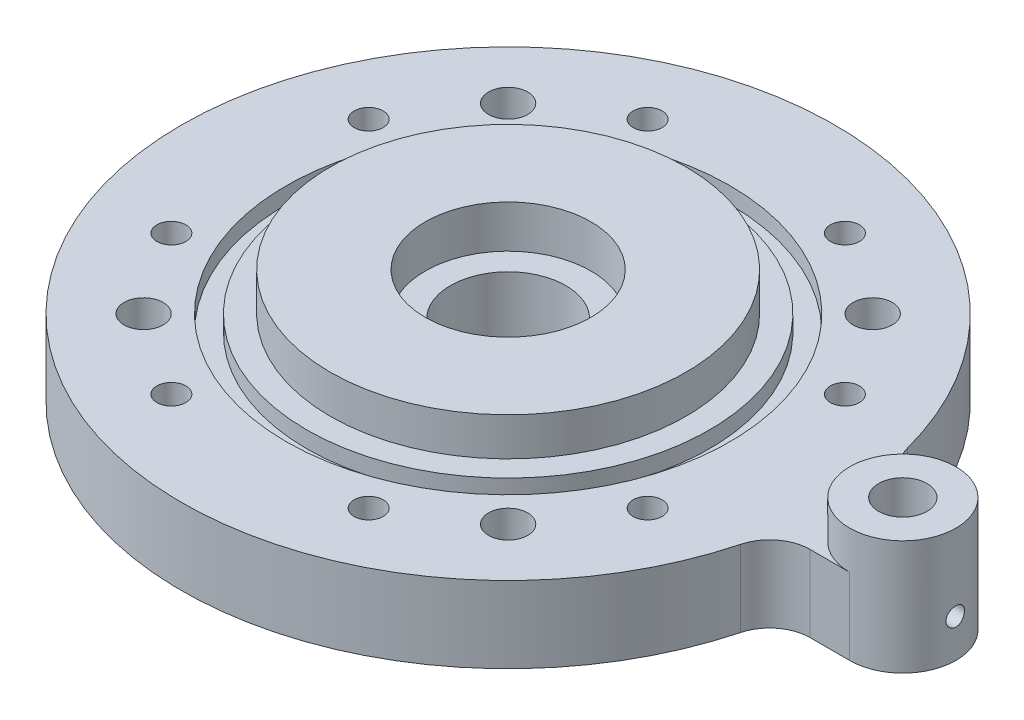
SolidWorks part; units mm, degrees
material "1060 Alloy"
ref_plane "Front" through (0, 0, 0) normal (0, 0, 1) x (1, 0, 0)
ref_plane "Top" through (0, 0, 0) normal (0, 1, 0) x (1, 0, 0)
ref_plane "Right" through (0, 0, 0) normal (1, 0, 0) x (0, 0, -1)
sketch "Sketch1" plane through (0, 0, 0) normal (0, 1, 0) x (1, 0, 0)
  line L0 (58.8962, 0) -> (68.0634, 0) construction
  line L1 (61.2588, 9.1672) -> (68.0634, 9.1672)
  line L2 (61.2588, -9.1672) -> (68.0634, -9.1672)
  line L3 (58.8962, 0) -> (77.2306, 0) construction
  line L4 (58.8962, 0) -> (56.3562, 0) construction
  arc A0 (54.4905, 14.3809) -> (54.4905, -14.3809) centre (0, 0) ccw
  circle A1 centre (0, 0) radius 56.3562 construction
  arc A2 (68.0634, -9.1672) -> (68.0634, 9.1672) centre (68.0634, 0) ccw
  arc A3 (54.4905, 14.3809) -> (61.2588, 9.1672) centre (61.2588, 16.1672) ccw
  arc A4 (61.2588, -9.1672) -> (54.4905, -14.3809) centre (61.2588, -16.1672) ccw
  point P5 (34.5422, 0)
  point P10 (55.6057, 9.1672)
  dimension "D1" = 112.7125
  dimension "D4" = 7
  dimension "D2" = 18.3344
  dimension "D3" = 18.3344
  dimension "D5" = 2.54
extrude "base" add sketch "Sketch1" along normal blind 13.175
sketch "Sketch2" plane through (0, 13.175, 0) normal (0, 1, 0) x (1, 0, 0)
  line L0 (68.0634, 9.1672) -> (68.0634, -9.1672) construction
  circle A0 centre (0, 0) radius 30.6705
  arc A1 (68.0634, -9.1672) -> (68.0634, 9.1672) centre (68.0634, 0) ccw construction
  circle A2 centre (68.0634, 0) radius 9.1672
  circle A3 centre (68.0634, 0) radius 4.1672
  dimension "D1" = 61.341
  dimension "D2" = 8.3344
sketch "Sketch3" plane through (0, 0, 0) normal (0, -1, 0) x (1, 0, 0)
  line L0 (0, 0) -> (77.2306, 0) construction
  line L1 (0, 0) -> (39.8499, -39.8499) construction
  circle A0 centre (0, 0) radius 44.45 construction
  circle A1 centre (-31.4309, -31.4309) radius 3.3734
  circle A2 centre (-31.4309, 31.4309) radius 3.3734
  circle A3 centre (31.4309, 31.4309) radius 3.3734
  circle A4 centre (31.4309, -31.4309) radius 3.3734
  arc A5 (68.0634, -9.1672) -> (68.0634, 9.1672) centre (68.0634, 0) ccw construction
  arc A6 (54.4905, 14.3809) -> (54.4905, -14.3809) centre (0, 0) ccw construction
  point P14 (0, 0)
  dimension "D1" = 88.9
  dimension "D2" = 6.7469
  dimension "D4" = 45
  dimension "D3" = 4
extrude "square bolt holes" cut sketch "Sketch3" against normal through all
sketch "Sketch4" plane through (0, 13.175, 0) normal (0, 1, 0) x (1, 0, 0)
  line L0 (0, 0) -> (0, 44.45) construction
  line L1 (0, 44.45) -> (0, 0) construction
  line L2 (0, 0) -> (17.0103, 41.0664) construction
  circle A0 centre (0, 0) radius 44.45 construction
  circle A1 centre (17.0103, 41.0664) radius 2.5
  dimension "D1" = 88.9
  dimension "D3" = 5
  dimension "D2" = 22.5
extrude "housing bolts" cut sketch "Sketch4" against normal blind 44.33
pattern_circular "CirPattern1" count 8 over 360 about axis through (0, 0, 0) along (0, 1, 0) of "housing bolts"
extrude "impeller cavity riser" add sketch "Sketch2" along normal blind 6.59
sketch "Sketch5" plane through (0, 19.765, 0) normal (0, 1, 0) x (1, 0, 0)
  circle A0 centre (0, 0) radius 14.2875
  dimension "D1" = 28.575
extrude "seal bore" cut sketch "Sketch5" against normal blind 7.35
sketch "Sketch6" plane through (0, 12.415, 0) normal (0, 1, 0) x (1, 0, 0)
  circle A0 centre (0, 0) radius 9.9375
  dimension "D1" = 19.875
extrude "bore" cut sketch "Sketch6" against normal blind 39.3
sketch "pressure tap plane alignment" plane through (0, 0, 0) normal (0, -1, 0) x (1, 0, 0)
  line L1 (0, 0) -> (56.3562, 0) construction
  line L2 (56.3562, 0) -> (56.3562, 56.3563) construction
  line L3 (56.3562, 56.3563) -> (0, 56.3562) construction
  circle A0 centre (0, 0) radius 56.3562 construction
  circle A1 centre (0, 0) radius 56.3562 construction
ref_plane "pressure tap plane" through (56.3562, 0, 0) normal (1, 0, 0) x (0, 0, -1)
sketch "Sketch9" plane through (56.3562, 0, 0) normal (1, 0, 0) x (0, 0, -1)
  line L0 (0, 0) -> (0, 13.175) construction
  line L1 (56.3562, 13.175) -> (-56.3563, 13.175) construction
  circle A0 centre (0, 6.5875) radius 1.5875
  dimension "D1" = 3.175
extrude "pressure tap" cut sketch "Sketch9" against normal blind 56.3562 and the other way through all
sketch "Sketch10" plane through (0, 13.175, 0) normal (0, 1, 0) x (1, 0, 0)
  circle A0 centre (68.0634, 0) radius 1.5875
  dimension "D1" = 3.175
extrude "pressure tap vertical hole" cut sketch "Sketch10" against normal blind 8.175
sketch "Sketch12" plane through (0, 13.175, 0) normal (0, 1, 0) x (1, 0, 0)
  circle A0 centre (0, 0) radius 34.7218
  circle A1 centre (0, 0) radius 38.2524
  dimension "D1" = 76.5048
  dimension "D2" = 69.4436
extrude "Cut-Extrude1" cut sketch "Sketch12" against normal blind 2.8245
equation "\"de\" = 0.43in\t\t\t'entrance eye diameter"
equation "\"d2\" = 2.1in \t\t\t'outer diameter of the impeller"
equation "\"d_exit\" = 0.18in \t\t'throat aka d1"
equation "\"theta\" = 12\t\t\t'angle of blades from inner to outer "
equation "\"impeller upper clearance\"= .5mm"
equation "\"impeller horizontal clearance\"= (\"d2\"*1.15 - \"d2\")/2 \t\t'clearance based on D2-D3 ratio for circular volute, ranges 1.15 to 1.2"
equation "\"impeller bottom clearance\"= .5mm"
equation "\"impeller base thickness\"= 2mm"
equation "\"impeller dowel diameter\" = 2mm"
equation "\"impeller bolt head diameter\" = \"m4 head bore diameter\""
equation "\"impeller bolt head depth\" = 4mm"
equation "\"impeller bolt stop depth\" = 3mm"
equation "\"impeller bolt bore\" = \"m4 clearance\""
equation "\"impeller shaft bore depth\" = 12mm"
equation "\"impeller shaft bore\" = 8mm"
equation "\"impeller boss depth\" = \"impeller shaft bore depth\"+\"impeller bolt stop depth\"+\"impeller bolt head depth\"-\"impeller base thickness\""
equation "\"impeller boss diameter\" = \"upper seal ID\""
equation "\"impeller dowel length\" = 2mm*2 + \"impeller shaft bore\""
equation "\"coupler motor shaft hole ID\"= 8mm"
equation "\"coupler OD\"= 17mm"
equation "\"coupler length\"= 25mm"
equation "\"motor OD\" = 64mm"
equation "\"motor shaft diameter\"= 8mm"
equation "\"motor shaft pride\"= 32mm"
equation "\"motor to bearing plate distance\" = \"motor shaft pride\" + 2mm +\"coupler length\"/2"
equation "\"square plate bolt bore\" = \"m8 clearance\""
equation "\"square plate bolt head diameter\" = 13.5mm"
equation "\"square plate bolt pattern diameter\"= 3.5in"
equation "\"motor mount center bore\"= \"coupler OD\"+ 4mm"
equation "\"motor mount post radius\"= ( 3 * \"square plate bolt bore\" ) / 2"
equation "\"motor mount m4 screw hole diameter\"= 4mm"
equation "\"motor mount m4 head diameter\"= 7.25mm"
equation "\"motor mount m4 head depth\"= 4mm"
equation "\"motor mount m4 pattern diamater\" = 30mm"
equation "\"motor mount plate thickness\"= 8mm + \"motor mount m4 head depth\""
equation "\"shaft coupler section diameter\" = 8mm"
equation "\"shaft coupler section length\" = \"motor to bearing plate distance\" - \"motor shaft pride\" - 2mm"
equation "\"shaft bearing section diameter\" = \"bearing ID\""
equation "\"shaft bearing section length\" = \"bearing plate stop depth\" + \"bearing depth\""
equation "\"shaft bearing stop diameter\" = \"bearing ID\" + 4mm"
equation "\"shaft bearing stop length\" = 3mm"
equation "\"impeller cavity center height\"= \"impeller bottom clearance\" + \"impeller upper clearance\" + \"impeller center height\""
equation "\"impeller cavity diameter\"= 2 * \"impeller horizontal clearance\" + \"d2\" \t\t\t\t\t\t\t\t\t'called D3 analytically"
equation "\"impeller cavity outer height\"= \"impeller bottom clearance\" + \"impeller upper clearance\" + \"impeller base thickness\" + \"b2\" \t\t'this is height at impeller diameter d2, not at d3"
equation "\"impeller housing thickness\"= \"impeller housing exit threaded diameter\" + 2*\"impeller housing outlet grip\""
equation "\"impeller housing diameter\" = \"square plate bolt pattern diameter\" + 2*\"motor mount post radius\""
equation "\"impeller housing bolt count\" = 8"
equation "\"impeller housing bolt diameter\" = \"m6 clearance\""
equation "\"impeller housing bolt pattern diameter\" = 3.5in"
equation "\"impeller housing threaded inlet diameter\" = 0.515625in \t'this is the 33/64 drill size for 9/16-18 fitting, expecting swagelok SS-8FK0-1-6STH fitting"
equation "\"impeller housing threaded inlet depth\"= 10mm"
equation "\"impeller housing exit threaded diameter\"= 0.515625in \t\t'this is the 33/64 drill size for 9/16-18 fitting, expecting swagelok SS-8FK0-1-6STH fitting"
equation "\"impeller housing exit threaded depth\"= 10mm"
equation "\"impeller housing diffuser conical angle\"=10"
equation "\"impeller housing diffuser tangent angle\"=5"
equation "\"impeller housing outlet grip\" = 5mm"
equation "\"D1@Sketch1\"=\"impeller housing diameter\""
equation "\"D1@base\" = \"upper seal plate thickness\""
equation "\"D1@Sketch2\"=\"impeller cavity diameter\""
equation "\"D1@Sketch3\"=\"square plate bolt pattern diameter\""
equation "\"D2@Sketch3\"=\"m8 tap\""
equation "\"D1\" = \"upper seal plate thickness\" - 2mm"
equation "\"D1@Sketch4\"=\"impeller housing bolt pattern diameter\""
equation "\"D2@Sketch4\"=360/\"impeller housing bolt count\"/2"
equation "\"D3@Sketch4\"=\"m6 tap\""
equation "\"D1@CirPattern1\"=\"impeller housing bolt count\""
equation "\"D1@impeller cavity riser\" = \"upper seal plate riser\""
equation "\"D1@Sketch5\" = \"upper seal OD\""
equation "\"D1@seal bore\" = \"upper seal bore\""
equation "\"D1@Sketch6\" = \"upper seal ID\" + 4mm"
equation "\"D1@Sketch9\" = \"upper seal plate pressure hole diameter\""
equation "\"D1@pressure tap\"=\"impeller housing diameter\"/2"
equation "\"de_length\" = 10mm\t\t'entrance eye consistent length"
equation "\"square plate bolt head depth\" = 8mm"
equation "\"shaft impeller section diameter\" = \"impeller shaft bore\""
equation "\"shaft impeller section length\" = \"upper seal plate thickness\" + \"upper seal plate riser\" + \"impeller bottom clearance\" + \"impeller base thickness\" - \"impeller bolt head depth\" - \"impeller bolt stop depth\""
equation "\"impeller housing diffuser final diameter\" = .38in"
equation "\"D2@Sketch1\" = \"upper seal plate pressure tap diameter\" + \"upper seal plate pressure tap grip\" * 2"
equation "\"D3@Sketch1\" = \"upper seal plate pressure tap diameter\" + \"upper seal plate pressure tap grip\" * 2"
equation "\"D2@pressure tap\"=\"big seal plate pressure tap diameter\"/2+\"big seal plate pressure tap grip\""
equation "\"D2@Sketch2\" = \"upper seal plate pressure tap diameter\""
equation "\"D1@Sketch10\" = \"upper seal plate pressure hole diameter\""
equation "\"D1@pressure tap vertical hole\"= \"upper seal plate thickness\" / 2 + \"upper seal plate pressure hole diameter\" / 2"
equation "\"end mill size\" = 0.375in\t'for 3/8 endmill"
equation "\"m6 clearance\" = 0.234375in\t'this is 15/64 bit = 5.95mm, could use 6mm bit, B bit for 6.04mm or 1/4 bit for 6.35mm"
equation "\"m6 tap\" = 5mm\t\t\t'5mm is appropriate, could use 13/64 or #5,6,7"
equation "\"m6 head bore diameter\" = 11mm\t\t"
equation "\"m6 head bore depth\" = 7mm\t'actual is 6mm"
equation "\"m8 clearance\" = 0.3125in\t'this is 5/16in for 7.93mm, could use 8mm, O,P, or 21/64"
equation "\"m8 tap\" = 0.265625in\t\t'this is 17/64 for 6.746875mm"
equation "\"m8 head bore diameter\" = 14mm"
equation "\"m8 head bore depth\" = 9mm\t'actual is 8mm"
equation "\"ce\" = 3.14*\"de\"\t\t'entrance eye circumference"
equation "\"s_open\" = \"av\"/\"b1\"\t\t'width of open area"
equation "\"impeller center height\" = \"impeller base thickness\" + \"b1\"\t'impeller height at de"
equation "\"impeller outer height\" = \"impeller base thickness\" + \"b2\"\t'impeller height at de"
equation "\"lower seal OD\" = .917in\t\t'this is https://www.mcmaster.com/#9281k121/=174001b"
equation "\"lower seal ID\"= .375in"
equation "\"lower seal depth\" = .625in + .218in"
equation "\"lower seal bore\" = \"lower seal depth\" + 1mm"
equation "\"upper seal OD\" = 1.125in\t'this is https://www.mcmaster.com/#5154t33/=173zuau, needs to be visually inspected before machining!"
equation "\"upper seal ID\"= 0.625in"
equation "\"upper seal depth\"= .25in\t'aka height; these values need to be confirmed by inspection!! We may want to compress the height."
equation "\"upper seal bore\" = \"upper seal depth\" + 1mm"
equation "\"lower seal plate lip depth\" = 2mm"
equation "\"lower seal plate lip ID\" = \"lower seal OD\" - 3mm"
equation "\"lower seal plate thickness\" = \"lower seal plate lip depth\" + \"lower seal bore\""
equation "\"shaft lower seal section diameter\" = \"lower seal ID\""
equation "\"shaft lower seal section length\" = \"lower seal plate thickness\" + 1mm"
equation "\"upper seal plate thickness\" = \"upper seal plate pressure hole diameter\"+10mm"
equation "\"upper seal plate lip ID\" = \"upper seal OD\" - 3mm"
equation "\"upper seal plate riser\" = 6.59mm \t\t'this number needs to be read from the housing file"
equation "\"upper seal plate pressure hole diameter\" = .125in\t'this is 1/8 drill "
equation "\"upper seal plate pressure tap diameter\" = .328125in \t'this is 21/64 drill for a 1/8 ANPT tap"
equation "\"upper seal plate pressure tap grip\" = 5mm\t\t'this is the area around the tap so it doesn't crack"
equation "\"upper seal plate pressure tap depth\" = 12"
equation "\"bearing OD\" = 30mm"
equation "\"bearing ID\"= 10mm"
equation "\"bearing depth\"= 9mm"
equation "\"bearing outer race thickness\"= 1mm"
equation "\"bearing inner race thickness\"= 1mm"
equation "\"bearing bore\" = \"bearing depth\" + 1mm"
equation "\"z\" = 8\t\t\t\t'number of blades"
equation "\"b2\" = .2in\t\t\t'tip height from disc surface at d2; slightly higher than d_exit"
equation "\"b1\" = \"b2\" + (\"d2\"/2 - \"de\"/2)*tan(\"theta\") \t\t\t'tip height from disc surface at inlet eye"
equation "\"ae\" = 3.14*(\"de\"^2)/4\t\t'entrance eye area'"
equation "\"av_ratio\" = .325\t\t'ratio of av/ae at N_s of 470, range is .275 to .375, .325 ideal. High ratio means bigger area means smaller blades"
equation "\"av\" = \"ae\"*\"av_ratio\"\t\t'area between just two blades"
equation "\"s\"=\"ce\" - \"z\"*\"s_open\""
equation "\"bearing plate stop ID\" = \"bearing OD\" - 4mm"
equation "\"bearing plate stop depth\" = 3mm"
equation "\"bearing plate thickness\" = \"bearing bore\" + \"bearing plate stop depth\" + \"shaft bearing stop length\""
equation "\"m4 clearance\" = 0.171875in \t'this is 11/64 bit for 4.36mm"
equation "\"m4 tap\" = 0.125in\t\t'this is 1/8 bit for 3.17mm"
equation "\"m4 head bore diameter\" = 7.5mm"
equation "\"m4 head bore depth\" = 5mm\t'actual is ~4mm"
equation "\"big o-ring thickness\" = .139in"
equation "\"big o-ring OD\" = 2.734in"
equation "\"big o-ring ID\" = 3.012in"
equation "\"big o-ring groove depth\" = \"big o-ring thickness\"*4/5"
equation "\"D1@Sketch12\"=\"big o-ring ID\""
equation "\"D2@Sketch12\"=\"big o-ring OD\""
equation "\"D1@Cut-Extrude1\"=\"big o-ring groove depth\""
equation "\"min blade thickness\" = .15in"
